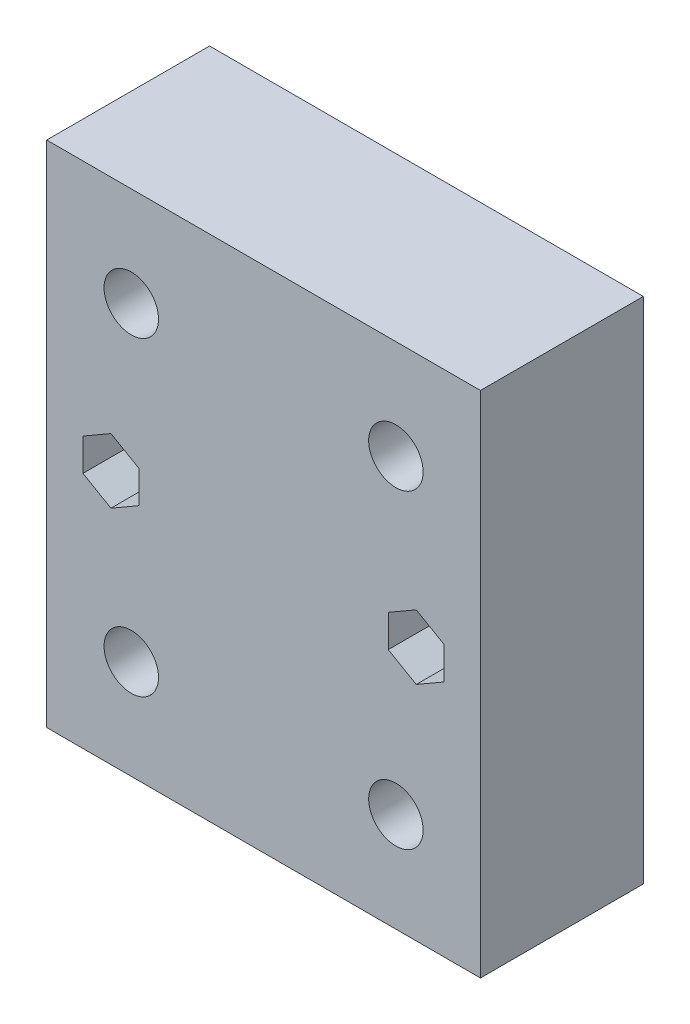
SolidWorks part; units mm, degrees
other "Markup1"
sketch "Sketch8" plane through (21.3115, 25, 0) normal (0.306, 0.1864, -0.9336) x (-0.9512, 0.0181, -0.3081)
ref_plane "Front Plane" through (0, 0, 0) normal (0, 0, 1) x (1, 0, 0)
ref_plane "Top Plane" through (0, 0, 0) normal (0, 1, 0) x (1, 0, 0)
ref_plane "Right Plane" through (0, 0, 0) normal (1, 0, 0) x (0, 0, -1)
sketch "Sketch1" plane through (0, 0, 0) normal (0, 0, 1) x (1, 0, 0)
  line L0 (0, 25) -> (0, -25) construction
  line L1 (21.3115, 25) -> (-21.3115, 25)
  line L2 (21.3115, 25) -> (21.3115, -25)
  line L3 (21.3115, -25) -> (-21.3115, -25)
  line L4 (-21.3115, 25) -> (-21.3115, -25)
  line L5 (21.3115, 25) -> (-21.3115, -25) construction
  line L6 (21.3115, -25) -> (-21.3115, 25) construction
  line L7 (-21.3115, 0) -> (21.3115, 0) construction
  circle A0 centre (-13, -15.25) radius 2.677
  circle A1 centre (13, -15.25) radius 2.677
  circle A2 centre (13, 15.25) radius 2.677
  circle A3 centre (-13, 15.25) radius 2.677
  point P0 (0, 0)
  dimension "D1" = 30.5
  dimension "D2" = 26
  dimension "D3" = 50
extrude "Boss-Extrude1" add sketch "Sketch1" along normal blind 16
sketch "Sketch2" plane through (0, 0, 0) normal (0, 0, 1) x (1, 0, 0)
  circle A0 centre (0, 0) radius 11
  dimension "D1" = 22
extrude "Cut-Extrude2" cut sketch "Sketch2" along normal blind 11
sketch "Sketch3" plane through (0, 0, 0) normal (0, 0, -1) x (-1, 0, 0)
  line L0 (0, 0) -> (-18.0234, 0) construction
  line L1 (0, 0) -> (0, 5.0894) construction
  circle A0 centre (-15, 0) radius 1.75
  circle A1 centre (15, 0) radius 1.75
  dimension "D1" = 15
  dimension "D2" = 3.5
extrude "Cut-Extrude3" cut sketch "Sketch3" against normal blind 10
sketch "Sketch6" plane through (0, -25, 0) normal (0, -1, 0) x (1, 0, 0)
  line L1 (4.517, 11) -> (-4.517, 11)
  line L2 (4.517, 11) -> (4.517, 13.3875)
  line L3 (4.517, 13.3875) -> (-4.517, 13.3875)
  line L4 (-4.517, 11) -> (-4.517, 13.3875)
  line L5 (4.517, 11) -> (-4.517, 13.3875) construction
  line L6 (4.517, 13.3875) -> (-4.517, 11) construction
  point P0 (0, 12.1938)
  point P5 (0, 11)
  dimension "D1" = 11
extrude "Cut-Extrude5" cut sketch "Sketch6" against normal blind 20
sketch "Sketch9" plane through (0, 0, 0) normal (0, 0, -1) x (-1, 0, 0)
  line L0 (0, -11) -> (0, 11) construction
  line L1 (-15, 3.1754) -> (-17.75, 1.5877)
  line L2 (-17.75, 1.5877) -> (-17.75, -1.5877)
  line L3 (-17.75, -1.5877) -> (-15, -3.1754)
  line L4 (-15, -3.1754) -> (-12.25, -1.5877)
  line L5 (-12.25, -1.5877) -> (-12.25, 1.5877)
  line L6 (-12.25, 1.5877) -> (-15, 3.1754)
  line L7 (12.25, 1.5877) -> (15, 3.1754)
  line L8 (12.25, -1.5877) -> (12.25, 1.5877)
  line L9 (15, -3.1754) -> (12.25, -1.5877)
  line L10 (17.75, -1.5877) -> (15, -3.1754)
  line L11 (17.75, 1.5877) -> (17.75, -1.5877)
  line L12 (15, 3.1754) -> (17.75, 1.5877)
  circle A0 centre (-15, 0) radius 2.75 construction
  circle A1 centre (0, 0) radius 11 construction
  point P1 (-17.75, 0)
  dimension "D1" = 5.5
extrude "Cut-Extrude6" cut sketch "Sketch9" against normal through all from offset 5
